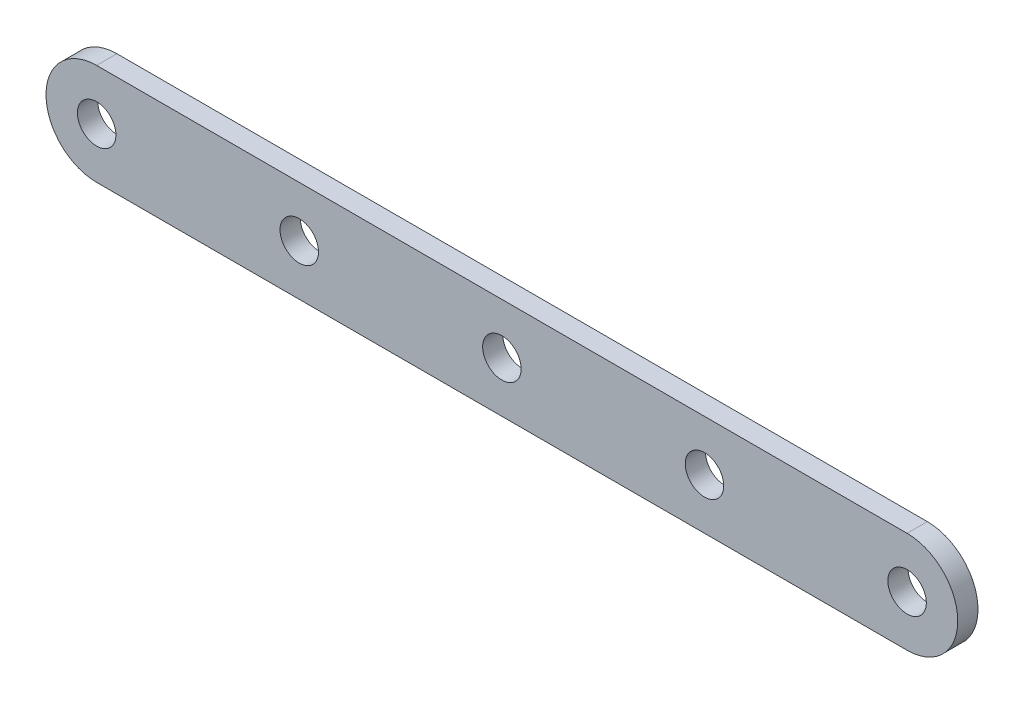
SolidWorks part; units mm, degrees
material "6061 Alloy"
ref_plane "Front" through (0, 0, 0) normal (0, 0, 1) x (1, 0, 0)
ref_plane "Top" through (0, 0, 0) normal (0, 1, 0) x (1, 0, 0)
ref_plane "Right" through (0, 0, 0) normal (1, 0, 0) x (0, 0, -1)
sketch "Sketch1" plane through (0, 0, 0) normal (0, 0, 1) x (1, 0, 0)
  line L0 (50.8, -6.35) -> (-50.8, 6.35) construction
  line L1 (-50.8, 6.35) -> (50.8, 6.35)
  line L2 (-50.8, 0) -> (50.8, 0) construction
  line L3 (-50.8, -6.35) -> (50.8, -6.35)
  arc A0 (50.8, 6.35) -> (50.8, -6.35) centre (50.8, 0) cw
  arc A1 (-50.8, 6.35) -> (-50.8, -6.35) centre (-50.8, 0) ccw
  dimension "D2" = 6.35
  dimension "D1" = 101.6
extrude "Boss-Extrude1" add sketch "Sketch1" along normal mid plane 2.54
sketch "Sketch2" plane through (0, 0, 1.27) normal (0, 0, 1) x (1, 0, 0)
  circle A0 centre (-50.8, 0) radius 2.413
  dimension "D1" = 4.826
extrude "Cut-Extrude1" cut sketch "Sketch2" against normal through all
pattern_linear "LPattern1" count 5 spacing 25.4 along (1, 0, 0) of "Cut-Extrude1"
